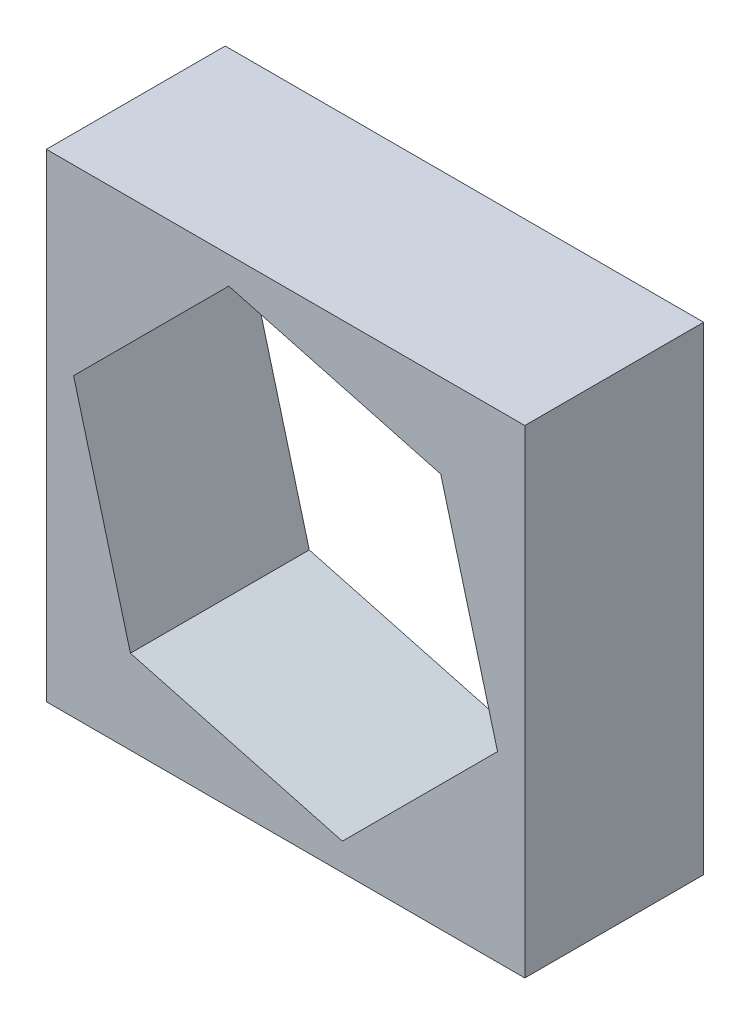
SolidWorks part; units mm, degrees
ref_plane "Спереди" through (0, 0, 0) normal (0, 0, 1) x (1, 0, 0)
ref_plane "Сверху" through (0, 0, 0) normal (0, 1, 0) x (1, 0, 0)
ref_plane "Справа" through (0, 0, 0) normal (1, 0, 0) x (0, 0, -1)
other "Configuration Table"
sketch "Эскиз1" plane through (0, 0, 0) normal (0, 0, 1) x (1, 0, 0)
  line L1 (-10.7, -10.7) -> (10.7, -10.7)
  line L2 (-10.7, -10.7) -> (-10.7, 10.7)
  line L3 (-10.7, 10.7) -> (10.7, 10.7)
  line L4 (10.7, -10.7) -> (10.7, 10.7)
  line L5 (-10.7, -10.7) -> (10.7, 10.7) construction
  line L6 (-10.7, 10.7) -> (10.7, -10.7) construction
  line L7 (-9.4805, 2.5403) -> (-6.9402, -6.9402)
  line L8 (-6.9402, -6.9402) -> (2.5403, -9.4805)
  line L9 (2.5403, -9.4805) -> (9.4805, -2.5403)
  line L10 (9.4805, -2.5403) -> (6.9402, 6.9402)
  line L11 (6.9402, 6.9402) -> (-2.5403, 9.4805)
  line L12 (-2.5403, 9.4805) -> (-9.4805, 2.5403)
  circle A0 centre (0, 0) radius 8.5 construction
  point P0 (0, 0)
  point P7 (-3.5694, 9.1429)
  point P15 (0, 0)
  dimension "D1" = 21.4
  dimension "D2" = 17
extrude "Бобышка-Вытянуть1" add sketch "Эскиз1" along normal blind 8
